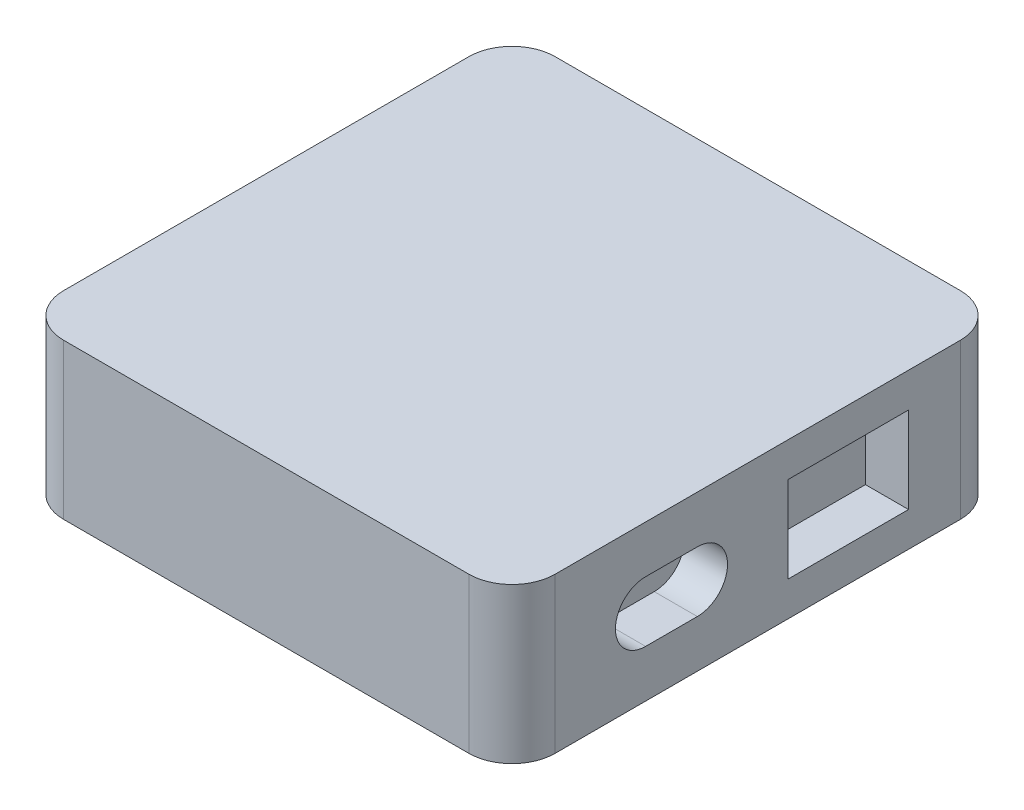
SolidWorks part; units mm, degrees
ref_plane "Alzado" through (0, 0, 0) normal (0, 0, 1) x (1, 0, 0)
ref_plane "Planta" through (0, 0, 0) normal (0, 1, 0) x (1, 0, 0)
ref_plane "Vista lateral" through (0, 0, 0) normal (1, 0, 0) x (0, 0, -1)
sketch "Croquis1" plane through (0, 0, 0) normal (0, 1, 0) x (1, 0, 0)
  line L1 (28.5, -28.5) -> (-28.5, -28.5)
  line L2 (28.5, -28.5) -> (28.5, 28.5)
  line L3 (28.5, 28.5) -> (-28.5, 28.5)
  line L4 (-28.5, -28.5) -> (-28.5, 28.5)
  line L5 (28.5, -28.5) -> (-28.5, 28.5) construction
  line L6 (28.5, 28.5) -> (-28.5, -28.5) construction
  point P0 (0, 0)
  dimension "D1" = 57
  dimension "D2" = 57
extrude "Saliente-Extruir1" add sketch "Croquis1" along normal blind 18
fillet "Redondeo1" radius 5 4 edges at (-28.5, 9, -28.5) (28.5, 9, -28.5) (-28.5, 9, 28.5) (28.5, 9, 28.5)
ref_plane "Plano1" through (0, 9, 0) normal (0, 1, 0) x (1, 0, 0)
sketch "Croquis2" plane through (28.5, 0, 0) normal (1, 0, 0) x (0, 0, -1)
  line L0 (-13, 9) -> (-7, 9) construction
  line L1 (31.35, 9) -> (-31.35, 9) construction
  line L2 (-13, 12.5) -> (-7, 12.5)
  line L3 (-13, 5.5) -> (-7, 5.5)
  line L4 (-28.5, 0) -> (-28.5, 18) construction
  line L6 (3.5, 14) -> (17.5, 14)
  line L7 (3.5, 14) -> (3.5, 4)
  line L8 (3.5, 4) -> (17.5, 4)
  line L9 (17.5, 14) -> (17.5, 4)
  arc A0 (-13, 12.5) -> (-13, 5.5) centre (-13, 9) ccw
  arc A1 (-7, 5.5) -> (-7, 12.5) centre (-7, 9) ccw
  point P4 (-10, 9)
  point P9 (3.5, 9)
  dimension "D2" = 7
  dimension "D1" = 18.5
  dimension "D3" = 6
  dimension "D4" = 32
  dimension "D5" = 14
  dimension "D6" = 10
extrude "Cortar-Extruir1" cut sketch "Croquis2" against normal blind 5
